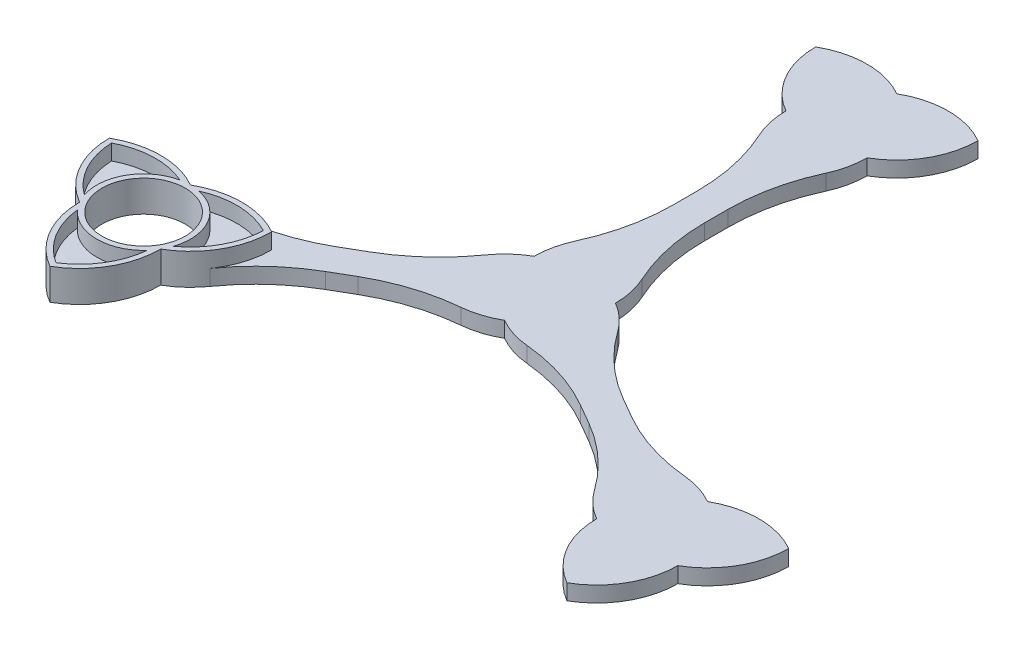
SolidWorks part; units mm, degrees
ref_plane "Front Plane" through (0, 0, 0) normal (0, 0, 1) x (1, 0, 0)
ref_plane "Top Plane" through (0, 0, 0) normal (0, 1, 0) x (1, 0, 0)
ref_plane "Right Plane" through (0, 0, 0) normal (1, 0, 0) x (0, 0, -1)
sketch "Sketch3" plane through (0, 0, 0) normal (0, 1, 0) x (1, 0, 0)
  line L0 (24.8205, 42.9904) -> (17.3205, 30) construction
  line L4 (0, 75.3205) -> (-15.5885, 48.3205) construction
  line L5 (-15.5885, 48.3205) -> (15.5885, 48.3205) construction
  line L6 (15.5885, 48.3205) -> (0, 75.3205) construction
  line L7 (-3, 83.7206) -> (-3, 85.9808)
  line L8 (3, 83.7206) -> (3, 85.9808)
  line L9 (24.8205, 42.9904) -> (26.3205, 45.5885) construction
  line L10 (15.5885, 48.3205) -> (24.8205, 42.9904) construction
  line L11 (24.3632, 46.7185) -> (26.3205, 45.5885)
  line L12 (21.3632, 41.5224) -> (23.3205, 40.3923)
  line L13 (0, 57.3205) -> (0, 40) construction
  line L14 (-21.3632, 41.5224) -> (-23.3205, 40.3923)
  line L15 (-24.3632, 46.7185) -> (-26.3205, 45.5885)
  line L17 (28.2778, 44.4584) -> (26.3205, 45.5885)
  line L18 (65.2295, 37.6603) -> (34.0526, 37.6603) construction
  line L19 (34.0526, 37.6603) -> (49.641, 10.6603) construction
  line L20 (49.641, 10.6603) -> (65.2295, 37.6603) construction
  line L21 (25.2778, 39.2622) -> (23.3205, 40.3923)
  line L25 (-3, 88.2409) -> (-3, 85.9808)
  line L26 (3, 88.2409) -> (3, 85.9808)
  line L27 (0, 85.9808) -> (15, 85.9808) construction
  line L32 (0, 85.9808) -> (-3, 85.9808) construction
  line L33 (-15.5885, 123.641) -> (0, 96.641) construction
  line L34 (0, 96.641) -> (15.5885, 123.641) construction
  line L39 (15.5885, 123.641) -> (-15.5885, 123.641) construction
  line L40 (0, 75.3205) -> (0, 85.9808) construction
  line L41 (0, 57.3205) -> (6.3532, 46.2988) construction
  line L44 (-28.2778, 44.4584) -> (-26.3205, 45.5885)
  line L46 (-65.2295, 37.6603) -> (-49.641, 10.6603) construction
  line L47 (-49.641, 10.6603) -> (-34.0526, 37.6603) construction
  line L48 (-34.0526, 37.6603) -> (-65.2295, 37.6603) construction
  line L50 (-25.2778, 39.2622) -> (-23.3205, 40.3923)
  line L51 (52.641, 2.2601) -> (52.641, 0) [skipped]
  line L52 (46.641, 2.2601) -> (46.641, 0) [skipped]
  line L53 (28.2778, -44.4584) -> (26.3205, -45.5885) [skipped]
  line L54 (52.641, -2.2601) -> (52.641, 0) [skipped]
  line L55 (46.641, -2.2601) -> (46.641, 0) [skipped]
  line L56 (25.2778, -39.2622) -> (23.3205, -40.3923) [skipped]
  line L57 (-24.3632, -46.7185) -> (-26.3205, -45.5885) [skipped]
  line L58 (24.3632, -46.7185) -> (26.3205, -45.5885) [skipped]
  line L59 (21.3632, -41.5224) -> (23.3205, -40.3923) [skipped]
  line L60 (-21.3632, -41.5224) -> (-23.3205, -40.3923) [skipped]
  line L61 (-52.641, -2.2601) -> (-52.641, 0) [skipped]
  line L62 (-28.2778, -44.4584) -> (-26.3205, -45.5885) [skipped]
  line L63 (-25.2778, -39.2622) -> (-23.3205, -40.3923) [skipped]
  line L64 (-46.641, -2.2601) -> (-46.641, 0) [skipped]
  line L65 (-52.641, 2.2601) -> (-52.641, 0) [skipped]
  line L66 (-46.641, 2.2601) -> (-46.641, 0) [skipped]
  line L67 (65.2295, -37.6603) -> (49.641, -10.6603) construction
  line L68 (49.641, -10.6603) -> (34.0526, -37.6603) construction
  line L69 (34.0526, -37.6603) -> (65.2295, -37.6603) construction
  line L70 (0, -75.3205) -> (15.5885, -48.3205) construction
  line L71 (15.5885, -48.3205) -> (-15.5885, -48.3205) construction
  line L72 (-15.5885, -48.3205) -> (0, -75.3205) construction
  line L73 (-34.0526, -37.6603) -> (-49.641, -10.6603) construction
  line L74 (-65.2295, -37.6603) -> (-34.0526, -37.6603) construction
  line L75 (-49.641, -10.6603) -> (-65.2295, -37.6603) construction
  line L76 (0, 57.3205) -> (6.3685, 68.3334) construction
  circle A1 centre (0, 57.3205) radius 9 construction
  arc A2 (0, 75.3205) -> (-7.7942, 61.8205) centre (7.7942, 61.8205) ccw
  arc A3 (0, 75.3205) -> (7.7942, 61.8205) centre (-7.7942, 61.8205) cw
  arc A4 (-12.7217, 57.3293) -> (-7.7942, 61.8205) centre (0, 48.3205) cw
  arc A5 (7.7942, 61.8205) -> (12.7217, 57.3293) centre (0, 48.3205) cw
  arc A6 (-7.7942, 61.8205) -> (7.7942, 61.8205) centre (0, 48.3205) cw construction
  arc A7 (0, 48.3205) -> (6.3532, 46.2988) centre (7.7942, 61.8205) ccw
  arc A8 (-7.7942, 61.8205) -> (0, 48.3205) centre (7.7942, 61.8205) ccw construction
  arc A9 (0, 48.3205) -> (-6.3532, 46.2988) centre (-7.7942, 61.8205) cw
  arc A10 (7.7942, 61.8205) -> (0, 48.3205) centre (-7.7942, 61.8205) cw construction
  arc A11 (12.7217, 57.3293) -> (24.3632, 46.7185) centre (42.7775, 78.6131) ccw
  arc A12 (6.3532, 46.2988) -> (21.3632, 41.5224) centre (2.9488, 9.6278) cw
  arc A13 (-6.3532, 46.2988) -> (-21.3632, 41.5224) centre (-2.9488, 9.6278) ccw
  arc A14 (-12.7217, 57.3293) -> (-24.3632, 46.7185) centre (-42.7775, 78.6131) cw
  arc A15 (12.7217, 57.3293) -> (15.5885, 48.3205) centre (0, 48.3205) cw construction
  arc A16 (6.3532, 46.2988) -> (15.5885, 48.3205) centre (7.7942, 61.8205) ccw construction
  arc A17 (-6.3532, 46.2988) -> (-15.5885, 48.3205) centre (-7.7942, 61.8205) cw construction
  arc A18 (-15.5885, 48.3205) -> (-12.7217, 57.3293) centre (0, 48.3205) cw construction
  arc A19 (65.2295, 37.6603) -> (49.641, 37.6603) centre (57.4352, 24.1603) ccw
  arc A20 (65.2295, 37.6603) -> (57.4352, 24.1603) centre (49.641, 37.6603) cw
  arc A21 (43.2878, 39.682) -> (49.641, 37.6603) centre (41.8468, 24.1603) cw
  arc A22 (57.4352, 24.1603) -> (56.0095, 17.6473) centre (41.8468, 24.1603) cw
  arc A23 (41.8468, 24.1603) -> (43.2726, 17.6473) centre (57.4352, 24.1603) ccw
  arc A24 (41.8468, 24.1603) -> (36.9193, 28.6515) centre (49.641, 37.6603) cw
  arc A27 (36.9193, 28.6515) -> (25.2778, 39.2622) centre (6.8635, 7.3677) ccw
  arc A28 (43.2878, 39.682) -> (28.2778, 44.4584) centre (46.6922, 76.353) cw
  circle A29 centre (49.641, 28.6603) radius 9 construction
  arc A30 (49.641, 37.6603) -> (57.4352, 24.1603) centre (41.8468, 24.1603) cw construction
  arc A31 (49.641, 37.6603) -> (41.8468, 24.1603) centre (57.4352, 24.1603) ccw construction
  arc A32 (57.4352, 24.1603) -> (41.8468, 24.1603) centre (49.641, 37.6603) cw construction
  arc A33 (56.0095, 17.6473) -> (49.641, 10.6603) centre (41.8468, 24.1603) cw
  arc A34 (43.2726, 17.6473) -> (49.641, 10.6603) centre (57.4352, 24.1603) ccw
  arc A35 (36.9193, 28.6515) -> (34.0526, 37.6603) centre (49.641, 37.6603) cw construction
  arc A36 (34.0526, 37.6603) -> (43.2878, 39.682) centre (41.8468, 24.1603) cw construction
  arc A47 (-6.3685, 68.3334) -> (-3, 83.7206) centre (-39.8287, 83.7206) ccw
  arc A51 (6.3685, 68.3334) -> (3, 83.7206) centre (39.8287, 83.7206) cw
  arc A52 (-15.5885, 123.641) -> (-7.7942, 110.141) centre (0, 123.641) ccw
  arc A53 (-15.5885, 123.641) -> (0, 123.641) centre (-7.7942, 110.141) cw
  arc A54 (-6.3685, 103.6281) -> (-7.7942, 110.141) centre (7.7942, 110.141) cw
  arc A65 (0, 123.641) -> (6.3532, 125.6627) centre (7.7942, 110.141) cw
  arc A69 (7.7942, 110.141) -> (12.7217, 114.6322) centre (0, 123.641) ccw
  arc A70 (7.7942, 110.141) -> (6.3685, 103.6281) centre (-7.7942, 110.141) cw
  arc A71 (6.3685, 103.6281) -> (3, 88.2409) centre (39.8287, 88.2409) ccw
  arc A72 (-6.3685, 103.6281) -> (-3, 88.2409) centre (-39.8287, 88.2409) cw
  circle A83 centre (0, 114.641) radius 9 construction
  arc A87 (-7.7942, 110.141) -> (0, 123.641) centre (7.7942, 110.141) cw construction
  arc A88 (-7.7942, 110.141) -> (7.7942, 110.141) centre (0, 123.641) ccw construction
  arc A89 (0, 123.641) -> (7.7942, 110.141) centre (-7.7942, 110.141) cw construction
  arc A90 (6.3532, 125.6627) -> (15.5885, 123.641) centre (7.7942, 110.141) cw
  arc A91 (-65.2295, 37.6603) -> (-57.4352, 24.1603) centre (-49.641, 37.6603) ccw
  arc A92 (-65.2295, 37.6603) -> (-49.641, 37.6603) centre (-57.4352, 24.1603) cw
  arc A93 (-56.0095, 17.6473) -> (-57.4352, 24.1603) centre (-41.8468, 24.1603) cw
  arc A94 (-49.641, 37.6603) -> (-43.2878, 39.682) centre (-41.8468, 24.1603) cw
  arc A95 (-41.8468, 24.1603) -> (-36.9193, 28.6515) centre (-49.641, 37.6603) ccw
  arc A96 (-41.8468, 24.1603) -> (-43.2726, 17.6473) centre (-57.4352, 24.1603) cw
  arc A97 (-43.2878, 39.682) -> (-28.2778, 44.4584) centre (-46.6922, 76.353) ccw
  arc A98 (-36.9193, 28.6515) -> (-25.2778, 39.2622) centre (-6.8635, 7.3677) cw
  circle A101 centre (-49.641, 28.6603) radius 9 construction
  arc A102 (-57.4352, 24.1603) -> (-49.641, 37.6603) centre (-41.8468, 24.1603) cw construction
  arc A103 (-57.4352, 24.1603) -> (-41.8468, 24.1603) centre (-49.641, 37.6603) ccw construction
  arc A104 (-49.641, 37.6603) -> (-41.8468, 24.1603) centre (-57.4352, 24.1603) cw construction
  arc A105 (-43.2878, 39.682) -> (-34.0526, 37.6603) centre (-41.8468, 24.1603) cw construction
  arc A106 (-36.9193, 28.6515) -> (-34.0526, 37.6603) centre (-49.641, 37.6603) ccw construction
  arc A107 (-43.2726, 17.6473) -> (-49.641, 10.6603) centre (-57.4352, 24.1603) cw
  arc A108 (-49.641, 10.6603) -> (-56.0095, 17.6473) centre (-41.8468, 24.1603) cw
  arc A109 (65.2295, -37.6603) -> (57.4352, -24.1603) centre (49.641, -37.6603) ccw [skipped]
  arc A110 (65.2295, -37.6603) -> (49.641, -37.6603) centre (57.4352, -24.1603) cw [skipped]
  arc A111 (56.0095, -17.6473) -> (57.4352, -24.1603) centre (41.8468, -24.1603) cw [skipped]
  arc A112 (49.641, -37.6603) -> (43.2878, -39.682) centre (41.8468, -24.1603) cw [skipped]
  arc A113 (41.8468, -24.1603) -> (36.9193, -28.6515) centre (49.641, -37.6603) ccw [skipped]
  arc A114 (41.8468, -24.1603) -> (43.2726, -17.6473) centre (57.4352, -24.1603) cw [skipped]
  arc A115 (43.2878, -39.682) -> (28.2778, -44.4584) centre (46.6922, -76.353) ccw [skipped]
  arc A116 (36.9193, -28.6515) -> (25.2778, -39.2622) centre (6.8635, -7.3677) cw [skipped]
  arc A117 (43.2726, -17.6473) -> (46.641, -2.2601) centre (9.8123, -2.2601) ccw [skipped]
  arc A118 (56.0095, -17.6473) -> (52.641, -2.2601) centre (89.4697, -2.2601) cw [skipped]
  arc A119 (0, -75.3205) -> (7.7942, -61.8205) centre (-7.7942, -61.8205) ccw [skipped]
  arc A120 (0, -75.3205) -> (-7.7942, -61.8205) centre (7.7942, -61.8205) cw [skipped]
  arc A121 (12.7217, -57.3293) -> (7.7942, -61.8205) centre (0, -48.3205) cw [skipped]
  arc A122 (-7.7942, -61.8205) -> (-12.7217, -57.3293) centre (0, -48.3205) cw [skipped]
  arc A123 (0, -48.3205) -> (-6.3532, -46.2988) centre (-7.7942, -61.8205) ccw [skipped]
  arc A124 (0, -48.3205) -> (6.3532, -46.2988) centre (7.7942, -61.8205) cw [skipped]
  arc A125 (-12.7217, -57.3293) -> (-24.3632, -46.7185) centre (-42.7775, -78.6131) ccw [skipped]
  arc A126 (-6.3532, -46.2988) -> (-21.3632, -41.5224) centre (-2.9488, -9.6278) cw [skipped]
  arc A127 (6.3532, -46.2988) -> (21.3632, -41.5224) centre (2.9488, -9.6278) ccw [skipped]
  arc A128 (12.7217, -57.3293) -> (24.3632, -46.7185) centre (42.7775, -78.6131) cw [skipped]
  arc A129 (-43.2878, -39.682) -> (-49.641, -37.6603) centre (-41.8468, -24.1603) cw [skipped]
  arc A130 (-57.4352, -24.1603) -> (-56.0095, -17.6473) centre (-41.8468, -24.1603) cw [skipped]
  arc A131 (-41.8468, -24.1603) -> (-43.2726, -17.6473) centre (-57.4352, -24.1603) ccw [skipped]
  arc A132 (-41.8468, -24.1603) -> (-36.9193, -28.6515) centre (-49.641, -37.6603) cw [skipped]
  arc A133 (-56.0095, -17.6473) -> (-52.641, -2.2601) centre (-89.4697, -2.2601) ccw [skipped]
  arc A134 (-43.2726, -17.6473) -> (-46.641, -2.2601) centre (-9.8123, -2.2601) cw [skipped]
  arc A135 (-36.9193, -28.6515) -> (-25.2778, -39.2622) centre (-6.8635, -7.3677) ccw [skipped]
  arc A136 (-43.2878, -39.682) -> (-28.2778, -44.4584) centre (-46.6922, -76.353) cw [skipped]
  circle A137 centre (49.641, -28.6603) radius 9 construction
  arc A138 (57.4352, -24.1603) -> (49.641, -37.6603) centre (41.8468, -24.1603) cw construction
  arc A139 (57.4352, -24.1603) -> (41.8468, -24.1603) centre (49.641, -37.6603) ccw construction
  arc A140 (49.641, -37.6603) -> (41.8468, -24.1603) centre (57.4352, -24.1603) cw construction
  arc A141 (43.2878, -39.682) -> (34.0526, -37.6603) centre (41.8468, -24.1603) cw construction
  arc A142 (36.9193, -28.6515) -> (34.0526, -37.6603) centre (49.641, -37.6603) ccw construction
  arc A143 (43.2726, -17.6473) -> (49.641, -10.6603) centre (57.4352, -24.1603) cw construction
  arc A144 (49.641, -10.6603) -> (56.0095, -17.6473) centre (41.8468, -24.1603) cw construction
  circle A145 centre (0, -57.3205) radius 9 construction
  arc A146 (7.7942, -61.8205) -> (-7.7942, -61.8205) centre (0, -48.3205) cw construction
  arc A147 (7.7942, -61.8205) -> (0, -48.3205) centre (-7.7942, -61.8205) ccw construction
  arc A148 (-7.7942, -61.8205) -> (0, -48.3205) centre (7.7942, -61.8205) cw construction
  arc A149 (-12.7217, -57.3293) -> (-15.5885, -48.3205) centre (0, -48.3205) cw construction
  arc A150 (-6.3532, -46.2988) -> (-15.5885, -48.3205) centre (-7.7942, -61.8205) ccw construction
  arc A151 (6.3532, -46.2988) -> (15.5885, -48.3205) centre (7.7942, -61.8205) cw construction
  arc A152 (15.5885, -48.3205) -> (12.7217, -57.3293) centre (0, -48.3205) cw construction
  circle A153 centre (-49.641, -28.6603) radius 9 construction
  arc A154 (-49.641, -37.6603) -> (-57.4352, -24.1603) centre (-41.8468, -24.1603) cw construction
  arc A155 (-49.641, -37.6603) -> (-41.8468, -24.1603) centre (-57.4352, -24.1603) ccw construction
  arc A156 (-57.4352, -24.1603) -> (-41.8468, -24.1603) centre (-49.641, -37.6603) cw construction
  arc A157 (-56.0095, -17.6473) -> (-49.641, -10.6603) centre (-41.8468, -24.1603) cw construction
  arc A158 (-43.2726, -17.6473) -> (-49.641, -10.6603) centre (-57.4352, -24.1603) ccw construction
  arc A159 (-36.9193, -28.6515) -> (-34.0526, -37.6603) centre (-49.641, -37.6603) cw construction
  arc A160 (-34.0526, -37.6603) -> (-43.2878, -39.682) centre (-41.8468, -24.1603) cw construction
  arc A161 (-65.2295, -37.6603) -> (-49.641, -37.6603) centre (-57.4352, -24.1603) ccw [skipped]
  arc A162 (-65.2295, -37.6603) -> (-57.4352, -24.1603) centre (-49.641, -37.6603) cw [skipped]
  arc A163 (-56.0095, 17.6473) -> (-52.641, 2.2601) centre (-89.4697, 2.2601) cw [skipped]
  arc A164 (-43.2726, 17.6473) -> (-46.641, 2.2601) centre (-9.8123, 2.2601) ccw [skipped]
  arc A165 (43.2726, 17.6473) -> (46.641, 2.2601) centre (9.8123, 2.2601) cw [skipped]
  arc A166 (56.0095, 17.6473) -> (52.641, 2.2601) centre (89.4697, 2.2601) ccw [skipped]
  arc A167 (12.7217, 114.6322) -> (15.5885, 123.641) centre (0, 123.641) ccw
  arc A168 (6.3685, 103.6281) -> (0, 96.641) centre (-7.7942, 110.141) cw construction
  arc A169 (0, 96.641) -> (-6.3685, 103.6281) centre (7.7942, 110.141) cw construction
  dimension "D1" = 18
  dimension "D2" = 6
  dimension "D3" = 3
  dimension "D4" = 2
  dimension "D5" = 120
extrude "Boss-Extrude2" add sketch "Sketch3" along normal blind 3 contours A108 A107 A96 A95 A98 L50 L14 A13 A9 A7 A12 L12 L21 A27 A24 A23 A34 A33 A22 A20 A19 A21 A28 L17 L11 A11 A5 A3 A2 A4 A14 L15 L44 A97 A94 A92 A91 A93 | A69 A167 A90 A65 A53 A52 A54 A72 L25 L7 A47 A2 A3 A51 L8 L26 A71 A70
ref_plane "Plane1" through (0, 3, 0) normal (0, 1, 0) x (1, 0, 0)
sketch "Sketch10" plane through (0, 3, 0) normal (0, 1, 0) x (1, 0, 0)
  line L0 (24.8205, 42.9904) -> (17.3205, 30) construction
  line L4 (0, 75.3205) -> (-15.5885, 48.3205) construction
  line L5 (-15.5885, 48.3205) -> (15.5885, 48.3205) construction
  line L6 (15.5885, 48.3205) -> (0, 75.3205) construction
  line L7 (-3, 83.7206) -> (-3, 85.9808)
  line L8 (3, 83.7206) -> (3, 85.9808)
  line L9 (24.8205, 42.9904) -> (26.3205, 45.5885) construction
  line L10 (15.5885, 48.3205) -> (24.8205, 42.9904) construction
  line L11 (24.3632, 46.7185) -> (26.3205, 45.5885)
  line L12 (21.3632, 41.5224) -> (23.3205, 40.3923)
  line L13 (0, 57.3205) -> (0, 40) construction
  line L14 (-21.3632, 41.5224) -> (-23.3205, 40.3923)
  line L15 (-24.3632, 46.7185) -> (-26.3205, 45.5885)
  line L17 (28.2778, 44.4584) -> (26.3205, 45.5885)
  line L18 (65.2295, 37.6603) -> (34.0526, 37.6603) construction
  line L19 (34.0526, 37.6603) -> (49.641, 10.6603) construction
  line L20 (49.641, 10.6603) -> (65.2295, 37.6603) construction
  line L21 (25.2778, 39.2622) -> (23.3205, 40.3923)
  line L25 (-3, 88.2409) -> (-3, 85.9808)
  line L26 (3, 88.2409) -> (3, 85.9808)
  line L27 (0, 85.9808) -> (15, 85.9808) construction
  line L32 (0, 85.9808) -> (-3, 85.9808) construction
  line L33 (-15.5885, 123.641) -> (0, 96.641) construction
  line L34 (0, 96.641) -> (15.5885, 123.641) construction
  line L39 (15.5885, 123.641) -> (-15.5885, 123.641) construction
  line L40 (0, 75.3205) -> (0, 85.9808) construction
  line L41 (0, 57.3205) -> (6.3532, 46.2988) construction
  line L44 (-28.2778, 44.4584) -> (-26.3205, 45.5885)
  line L46 (-65.2295, 37.6603) -> (-49.641, 10.6603) construction
  line L47 (-49.641, 10.6603) -> (-34.0526, 37.6603) construction
  line L48 (-34.0526, 37.6603) -> (-65.2295, 37.6603) construction
  line L50 (-25.2778, 39.2622) -> (-23.3205, 40.3923)
  line L51 (52.641, 2.2601) -> (52.641, 0)
  line L52 (46.641, 2.2601) -> (46.641, 0)
  line L53 (28.2778, -44.4584) -> (26.3205, -45.5885)
  line L54 (52.641, -2.2601) -> (52.641, 0)
  line L55 (46.641, -2.2601) -> (46.641, 0)
  line L56 (25.2778, -39.2622) -> (23.3205, -40.3923)
  line L57 (-24.3632, -46.7185) -> (-26.3205, -45.5885)
  line L58 (24.3632, -46.7185) -> (26.3205, -45.5885)
  line L59 (21.3632, -41.5224) -> (23.3205, -40.3923)
  line L60 (-21.3632, -41.5224) -> (-23.3205, -40.3923)
  line L61 (-52.641, -2.2601) -> (-52.641, 0)
  line L62 (-28.2778, -44.4584) -> (-26.3205, -45.5885)
  line L63 (-25.2778, -39.2622) -> (-23.3205, -40.3923)
  line L64 (-46.641, -2.2601) -> (-46.641, 0)
  line L65 (-52.641, 2.2601) -> (-52.641, 0)
  line L66 (-46.641, 2.2601) -> (-46.641, 0)
  line L67 (65.2295, -37.6603) -> (49.641, -10.6603) construction
  line L68 (49.641, -10.6603) -> (34.0526, -37.6603) construction
  line L69 (34.0526, -37.6603) -> (65.2295, -37.6603) construction
  line L70 (0, -75.3205) -> (15.5885, -48.3205) construction
  line L71 (15.5885, -48.3205) -> (-15.5885, -48.3205) construction
  line L72 (-15.5885, -48.3205) -> (0, -75.3205) construction
  line L73 (-34.0526, -37.6603) -> (-49.641, -10.6603) construction
  line L74 (-65.2295, -37.6603) -> (-34.0526, -37.6603) construction
  line L75 (-49.641, -10.6603) -> (-65.2295, -37.6603) construction
  line L76 (0, 57.3205) -> (6.3685, 68.3334) construction
  circle A1 centre (0, 57.3205) radius 9 construction
  arc A2 (0, 75.3205) -> (-7.7942, 61.8205) centre (7.7942, 61.8205) ccw
  arc A3 (0, 75.3205) -> (7.7942, 61.8205) centre (-7.7942, 61.8205) cw
  arc A4 (-12.7217, 57.3293) -> (-7.7942, 61.8205) centre (0, 48.3205) cw
  arc A5 (7.7942, 61.8205) -> (12.7217, 57.3293) centre (0, 48.3205) cw
  arc A6 (-7.7942, 61.8205) -> (7.7942, 61.8205) centre (0, 48.3205) cw construction
  arc A7 (0, 48.3205) -> (6.3532, 46.2988) centre (7.7942, 61.8205) ccw
  arc A8 (-7.7942, 61.8205) -> (0, 48.3205) centre (7.7942, 61.8205) ccw construction
  arc A9 (0, 48.3205) -> (-6.3532, 46.2988) centre (-7.7942, 61.8205) cw
  arc A10 (7.7942, 61.8205) -> (0, 48.3205) centre (-7.7942, 61.8205) cw construction
  arc A11 (12.7217, 57.3293) -> (24.3632, 46.7185) centre (42.7775, 78.6131) ccw
  arc A12 (6.3532, 46.2988) -> (21.3632, 41.5224) centre (2.9488, 9.6278) cw
  arc A13 (-6.3532, 46.2988) -> (-21.3632, 41.5224) centre (-2.9488, 9.6278) ccw
  arc A14 (-12.7217, 57.3293) -> (-24.3632, 46.7185) centre (-42.7775, 78.6131) cw
  arc A15 (12.7217, 57.3293) -> (15.5885, 48.3205) centre (0, 48.3205) cw construction
  arc A16 (6.3532, 46.2988) -> (15.5885, 48.3205) centre (7.7942, 61.8205) ccw construction
  arc A17 (-6.3532, 46.2988) -> (-15.5885, 48.3205) centre (-7.7942, 61.8205) cw construction
  arc A18 (-15.5885, 48.3205) -> (-12.7217, 57.3293) centre (0, 48.3205) cw construction
  arc A19 (65.2295, 37.6603) -> (49.641, 37.6603) centre (57.4352, 24.1603) ccw
  arc A20 (65.2295, 37.6603) -> (57.4352, 24.1603) centre (49.641, 37.6603) cw
  arc A21 (43.2878, 39.682) -> (49.641, 37.6603) centre (41.8468, 24.1603) cw
  arc A22 (57.4352, 24.1603) -> (56.0095, 17.6473) centre (41.8468, 24.1603) cw
  arc A23 (41.8468, 24.1603) -> (43.2726, 17.6473) centre (57.4352, 24.1603) ccw
  arc A24 (41.8468, 24.1603) -> (36.9193, 28.6515) centre (49.641, 37.6603) cw
  arc A27 (36.9193, 28.6515) -> (25.2778, 39.2622) centre (6.8635, 7.3677) ccw
  arc A28 (43.2878, 39.682) -> (28.2778, 44.4584) centre (46.6922, 76.353) cw
  circle A29 centre (49.641, 28.6603) radius 9 construction
  arc A30 (49.641, 37.6603) -> (57.4352, 24.1603) centre (41.8468, 24.1603) cw construction
  arc A31 (49.641, 37.6603) -> (41.8468, 24.1603) centre (57.4352, 24.1603) ccw construction
  arc A32 (57.4352, 24.1603) -> (41.8468, 24.1603) centre (49.641, 37.6603) cw construction
  arc A33 (56.0095, 17.6473) -> (49.641, 10.6603) centre (41.8468, 24.1603) cw
  arc A34 (43.2726, 17.6473) -> (49.641, 10.6603) centre (57.4352, 24.1603) ccw
  arc A35 (36.9193, 28.6515) -> (34.0526, 37.6603) centre (49.641, 37.6603) cw construction
  arc A36 (34.0526, 37.6603) -> (43.2878, 39.682) centre (41.8468, 24.1603) cw construction
  arc A47 (-6.3685, 68.3334) -> (-3, 83.7206) centre (-39.8287, 83.7206) ccw
  arc A51 (6.3685, 68.3334) -> (3, 83.7206) centre (39.8287, 83.7206) cw
  arc A52 (-15.5885, 123.641) -> (-7.7942, 110.141) centre (0, 123.641) ccw
  arc A53 (-15.5885, 123.641) -> (0, 123.641) centre (-7.7942, 110.141) cw
  arc A54 (-6.3685, 103.6281) -> (-7.7942, 110.141) centre (7.7942, 110.141) cw
  arc A65 (0, 123.641) -> (6.3532, 125.6627) centre (7.7942, 110.141) cw
  arc A69 (7.7942, 110.141) -> (12.7217, 114.6322) centre (0, 123.641) ccw
  arc A70 (7.7942, 110.141) -> (6.3685, 103.6281) centre (-7.7942, 110.141) cw
  arc A71 (6.3685, 103.6281) -> (3, 88.2409) centre (39.8287, 88.2409) ccw
  arc A72 (-6.3685, 103.6281) -> (-3, 88.2409) centre (-39.8287, 88.2409) cw
  circle A83 centre (0, 114.641) radius 9 construction
  arc A87 (-7.7942, 110.141) -> (0, 123.641) centre (7.7942, 110.141) cw construction
  arc A88 (-7.7942, 110.141) -> (7.7942, 110.141) centre (0, 123.641) ccw construction
  arc A89 (0, 123.641) -> (7.7942, 110.141) centre (-7.7942, 110.141) cw construction
  arc A90 (6.3532, 125.6627) -> (15.5885, 123.641) centre (7.7942, 110.141) cw
  arc A91 (-65.2295, 37.6603) -> (-57.4352, 24.1603) centre (-49.641, 37.6603) ccw
  arc A92 (-65.2295, 37.6603) -> (-49.641, 37.6603) centre (-57.4352, 24.1603) cw
  arc A93 (-56.0095, 17.6473) -> (-57.4352, 24.1603) centre (-41.8468, 24.1603) cw
  arc A94 (-49.641, 37.6603) -> (-43.2878, 39.682) centre (-41.8468, 24.1603) cw
  arc A95 (-41.8468, 24.1603) -> (-36.9193, 28.6515) centre (-49.641, 37.6603) ccw
  arc A96 (-41.8468, 24.1603) -> (-43.2726, 17.6473) centre (-57.4352, 24.1603) cw
  arc A97 (-43.2878, 39.682) -> (-28.2778, 44.4584) centre (-46.6922, 76.353) ccw
  arc A98 (-36.9193, 28.6515) -> (-25.2778, 39.2622) centre (-6.8635, 7.3677) cw
  circle A101 centre (-49.641, 28.6603) radius 9 construction
  arc A102 (-57.4352, 24.1603) -> (-49.641, 37.6603) centre (-41.8468, 24.1603) cw construction
  arc A103 (-57.4352, 24.1603) -> (-41.8468, 24.1603) centre (-49.641, 37.6603) ccw construction
  arc A104 (-49.641, 37.6603) -> (-41.8468, 24.1603) centre (-57.4352, 24.1603) cw construction
  arc A105 (-43.2878, 39.682) -> (-34.0526, 37.6603) centre (-41.8468, 24.1603) cw construction
  arc A106 (-36.9193, 28.6515) -> (-34.0526, 37.6603) centre (-49.641, 37.6603) ccw construction
  arc A107 (-43.2726, 17.6473) -> (-49.641, 10.6603) centre (-57.4352, 24.1603) cw
  arc A108 (-49.641, 10.6603) -> (-56.0095, 17.6473) centre (-41.8468, 24.1603) cw
  arc A109 (65.2295, -37.6603) -> (57.4352, -24.1603) centre (49.641, -37.6603) ccw
  arc A110 (65.2295, -37.6603) -> (49.641, -37.6603) centre (57.4352, -24.1603) cw
  arc A111 (56.0095, -17.6473) -> (57.4352, -24.1603) centre (41.8468, -24.1603) cw
  arc A112 (49.641, -37.6603) -> (43.2878, -39.682) centre (41.8468, -24.1603) cw
  arc A113 (41.8468, -24.1603) -> (36.9193, -28.6515) centre (49.641, -37.6603) ccw
  arc A114 (41.8468, -24.1603) -> (43.2726, -17.6473) centre (57.4352, -24.1603) cw
  arc A115 (43.2878, -39.682) -> (28.2778, -44.4584) centre (46.6922, -76.353) ccw
  arc A116 (36.9193, -28.6515) -> (25.2778, -39.2622) centre (6.8635, -7.3677) cw
  arc A117 (43.2726, -17.6473) -> (46.641, -2.2601) centre (9.8123, -2.2601) ccw
  arc A118 (56.0095, -17.6473) -> (52.641, -2.2601) centre (89.4697, -2.2601) cw
  arc A119 (0, -75.3205) -> (7.7942, -61.8205) centre (-7.7942, -61.8205) ccw
  arc A120 (0, -75.3205) -> (-7.7942, -61.8205) centre (7.7942, -61.8205) cw
  arc A121 (12.7217, -57.3293) -> (7.7942, -61.8205) centre (0, -48.3205) cw
  arc A122 (-7.7942, -61.8205) -> (-12.7217, -57.3293) centre (0, -48.3205) cw
  arc A123 (0, -48.3205) -> (-6.3532, -46.2988) centre (-7.7942, -61.8205) ccw
  arc A124 (0, -48.3205) -> (6.3532, -46.2988) centre (7.7942, -61.8205) cw
  arc A125 (-12.7217, -57.3293) -> (-24.3632, -46.7185) centre (-42.7775, -78.6131) ccw
  arc A126 (-6.3532, -46.2988) -> (-21.3632, -41.5224) centre (-2.9488, -9.6278) cw
  arc A127 (6.3532, -46.2988) -> (21.3632, -41.5224) centre (2.9488, -9.6278) ccw
  arc A128 (12.7217, -57.3293) -> (24.3632, -46.7185) centre (42.7775, -78.6131) cw
  arc A129 (-43.2878, -39.682) -> (-49.641, -37.6603) centre (-41.8468, -24.1603) cw
  arc A130 (-57.4352, -24.1603) -> (-56.0095, -17.6473) centre (-41.8468, -24.1603) cw
  arc A131 (-41.8468, -24.1603) -> (-43.2726, -17.6473) centre (-57.4352, -24.1603) ccw
  arc A132 (-41.8468, -24.1603) -> (-36.9193, -28.6515) centre (-49.641, -37.6603) cw
  arc A133 (-56.0095, -17.6473) -> (-52.641, -2.2601) centre (-89.4697, -2.2601) ccw
  arc A134 (-43.2726, -17.6473) -> (-46.641, -2.2601) centre (-9.8123, -2.2601) cw
  arc A135 (-36.9193, -28.6515) -> (-25.2778, -39.2622) centre (-6.8635, -7.3677) ccw
  arc A136 (-43.2878, -39.682) -> (-28.2778, -44.4584) centre (-46.6922, -76.353) cw
  circle A137 centre (49.641, -28.6603) radius 9 construction
  arc A138 (57.4352, -24.1603) -> (49.641, -37.6603) centre (41.8468, -24.1603) cw construction
  arc A139 (57.4352, -24.1603) -> (41.8468, -24.1603) centre (49.641, -37.6603) ccw construction
  arc A140 (49.641, -37.6603) -> (41.8468, -24.1603) centre (57.4352, -24.1603) cw construction
  arc A141 (43.2878, -39.682) -> (34.0526, -37.6603) centre (41.8468, -24.1603) cw construction
  arc A142 (36.9193, -28.6515) -> (34.0526, -37.6603) centre (49.641, -37.6603) ccw construction
  arc A143 (43.2726, -17.6473) -> (49.641, -10.6603) centre (57.4352, -24.1603) cw construction
  arc A144 (49.641, -10.6603) -> (56.0095, -17.6473) centre (41.8468, -24.1603) cw construction
  circle A145 centre (0, -57.3205) radius 9 construction
  arc A146 (7.7942, -61.8205) -> (-7.7942, -61.8205) centre (0, -48.3205) cw construction
  arc A147 (7.7942, -61.8205) -> (0, -48.3205) centre (-7.7942, -61.8205) ccw construction
  arc A148 (-7.7942, -61.8205) -> (0, -48.3205) centre (7.7942, -61.8205) cw construction
  arc A149 (-12.7217, -57.3293) -> (-15.5885, -48.3205) centre (0, -48.3205) cw construction
  arc A150 (-6.3532, -46.2988) -> (-15.5885, -48.3205) centre (-7.7942, -61.8205) ccw construction
  arc A151 (6.3532, -46.2988) -> (15.5885, -48.3205) centre (7.7942, -61.8205) cw construction
  arc A152 (15.5885, -48.3205) -> (12.7217, -57.3293) centre (0, -48.3205) cw construction
  circle A153 centre (-49.641, -28.6603) radius 9 construction
  arc A154 (-49.641, -37.6603) -> (-57.4352, -24.1603) centre (-41.8468, -24.1603) cw construction
  arc A155 (-49.641, -37.6603) -> (-41.8468, -24.1603) centre (-57.4352, -24.1603) ccw construction
  arc A156 (-57.4352, -24.1603) -> (-41.8468, -24.1603) centre (-49.641, -37.6603) cw construction
  arc A157 (-56.0095, -17.6473) -> (-49.641, -10.6603) centre (-41.8468, -24.1603) cw construction
  arc A158 (-43.2726, -17.6473) -> (-49.641, -10.6603) centre (-57.4352, -24.1603) ccw construction
  arc A159 (-36.9193, -28.6515) -> (-34.0526, -37.6603) centre (-49.641, -37.6603) cw construction
  arc A160 (-34.0526, -37.6603) -> (-43.2878, -39.682) centre (-41.8468, -24.1603) cw construction
  arc A161 (-65.2295, -37.6603) -> (-49.641, -37.6603) centre (-57.4352, -24.1603) ccw
  arc A162 (-65.2295, -37.6603) -> (-57.4352, -24.1603) centre (-49.641, -37.6603) cw
  arc A163 (-56.0095, 17.6473) -> (-52.641, 2.2601) centre (-89.4697, 2.2601) cw
  arc A164 (-43.2726, 17.6473) -> (-46.641, 2.2601) centre (-9.8123, 2.2601) ccw
  arc A165 (43.2726, 17.6473) -> (46.641, 2.2601) centre (9.8123, 2.2601) cw
  arc A166 (56.0095, 17.6473) -> (52.641, 2.2601) centre (89.4697, 2.2601) ccw
  arc A167 (12.7217, 114.6322) -> (15.5885, 123.641) centre (0, 123.641) ccw
  arc A168 (6.3685, 103.6281) -> (0, 96.641) centre (-7.7942, 110.141) cw construction
  arc A169 (0, 96.641) -> (-6.3685, 103.6281) centre (7.7942, 110.141) cw construction
  dimension "D1" = 18
  dimension "D2" = 6
  dimension "D3" = 3
  dimension "D4" = 2
  dimension "D5" = 120
sketch "Sketch12" plane through (0, 3, 0) normal (0, 1, 0) x (1, 0, 0)
  circle A0 centre (-49.641, 28.6603) radius 9 construction
  circle A1 centre (-49.641, 28.6603) radius 9 construction
  arc A2 (-57.4352, 24.1603) -> (-56.0095, 17.6473) centre (-41.8468, 24.1603) ccw construction
  arc A3 (-56.0095, 17.6473) -> (-49.641, 10.6603) centre (-41.8468, 24.1603) ccw construction
  arc A4 (-49.641, 10.6603) -> (-43.2726, 17.6473) centre (-57.4352, 24.1603) ccw construction
  arc A5 (-43.2726, 17.6473) -> (-41.8468, 24.1603) centre (-57.4352, 24.1603) ccw construction
  arc A6 (-41.8468, 24.1603) -> (-36.9193, 28.6515) centre (-49.641, 37.6603) ccw construction
  arc A7 (-36.9193, 28.6515) -> (-34.0526, 37.6603) centre (-49.641, 37.6603) ccw construction
  arc A8 (-34.0526, 37.6603) -> (-43.2878, 39.682) centre (-41.8468, 24.1603) ccw construction
  arc A9 (-43.2878, 39.682) -> (-49.641, 37.6603) centre (-41.8468, 24.1603) ccw construction
  arc A10 (-49.641, 37.6603) -> (-65.2295, 37.6603) centre (-57.4352, 24.1603) ccw construction
  arc A11 (-65.2295, 37.6603) -> (-57.4352, 24.1603) centre (-49.641, 37.6603) ccw construction
  arc A12 (-57.4352, 24.1603) -> (-56.0095, 17.6473) centre (-41.8468, 24.1603) ccw
  arc A13 (-56.0095, 17.6473) -> (-49.641, 10.6603) centre (-41.8468, 24.1603) ccw
  arc A14 (-49.641, 10.6603) -> (-43.2726, 17.6473) centre (-57.4352, 24.1603) ccw
  arc A15 (-43.2726, 17.6473) -> (-41.8468, 24.1603) centre (-57.4352, 24.1603) ccw
  arc A16 (-41.8468, 24.1603) -> (-36.9193, 28.6515) centre (-49.641, 37.6603) ccw
  arc A17 (-36.9193, 28.6515) -> (-34.0526, 37.6603) centre (-49.641, 37.6603) ccw
  arc A18 (-34.0526, 37.6603) -> (-43.2878, 39.682) centre (-41.8468, 24.1603) ccw
  arc A19 (-43.2878, 39.682) -> (-49.641, 37.6603) centre (-41.8468, 24.1603) ccw
  arc A20 (-49.641, 37.6603) -> (-65.2295, 37.6603) centre (-57.4352, 24.1603) ccw
  arc A21 (-65.2295, 37.6603) -> (-57.4352, 24.1603) centre (-49.641, 37.6603) ccw
  circle A22 centre (-49.641, 28.6603) radius 8
  circle A23 centre (-49.641, 28.6603) radius 9
  arc A24 (-64.2178, 37.0761) -> (-58.1866, 25.8367) centre (-49.641, 37.6603) ccw
  arc A25 (-56.4235, 24.7444) -> (-56.4327, 24.4326) centre (-41.8468, 24.1603) ccw construction
  arc A26 (-55.1009, 18.0651) -> (-49.641, 11.8285) centre (-41.8468, 24.1603) ccw
  arc A27 (-49.641, 11.8285) -> (-44.1811, 18.0651) centre (-57.4352, 24.1603) ccw
  arc A28 (-44.1811, 18.0651) -> (-42.923, 22.6713) centre (-57.4352, 24.1603) ccw
  arc A29 (-42.8585, 24.7444) -> (-42.5839, 24.8923) centre (-49.641, 37.6603) ccw construction
  arc A30 (-37.7354, 29.2294) -> (-35.0643, 37.0761) centre (-49.641, 37.6603) ccw
  arc A31 (-35.0643, 37.0761) -> (-43.1953, 38.6862) centre (-41.8468, 24.1603) ccw
  arc A32 (-43.1953, 38.6862) -> (-47.8134, 37.4727) centre (-41.8468, 24.1603) ccw
  arc A33 (-49.641, 36.492) -> (-49.9064, 36.6559) centre (-57.4352, 24.1603) ccw construction
  arc A34 (-56.6981, 24.8923) -> (-56.4235, 24.7444) centre (-49.641, 37.6603) ccw construction
  arc A35 (-56.3591, 22.6713) -> (-55.1009, 18.0651) centre (-41.8468, 24.1603) ccw
  arc A36 (-58.1866, 25.8367) -> (-56.6981, 24.8923) centre (-49.641, 37.6603) ccw construction
  arc A37 (-64.2178, 37.0761) -> (-56.4235, 24.7444) centre (-49.641, 37.6603) ccw construction
  arc A38 (-42.8493, 24.4326) -> (-42.8585, 24.7444) centre (-57.4352, 24.1603) ccw construction
  arc A39 (-56.4327, 24.4326) -> (-56.3591, 22.6713) centre (-41.8468, 24.1603) ccw construction
  arc A40 (-56.4235, 24.7444) -> (-55.1009, 18.0651) centre (-41.8468, 24.1603) ccw construction
  arc A41 (-41.0954, 25.8367) -> (-37.7354, 29.2294) centre (-49.641, 37.6603) ccw
  arc A42 (-42.923, 22.6713) -> (-42.8493, 24.4326) centre (-57.4352, 24.1603) ccw construction
  arc A43 (-44.1811, 18.0651) -> (-42.8585, 24.7444) centre (-57.4352, 24.1603) ccw construction
  arc A44 (-49.3756, 36.6559) -> (-49.641, 36.492) centre (-41.8468, 24.1603) ccw construction
  arc A45 (-42.5839, 24.8923) -> (-41.0954, 25.8367) centre (-49.641, 37.6603) ccw construction
  arc A46 (-42.8585, 24.7444) -> (-37.7354, 29.2294) centre (-49.641, 37.6603) ccw construction
  arc A47 (-51.4686, 37.4727) -> (-64.2178, 37.0761) centre (-57.4352, 24.1603) ccw
  arc A48 (-47.8134, 37.4727) -> (-49.3756, 36.6559) centre (-41.8468, 24.1603) ccw construction
  arc A49 (-43.1953, 38.6862) -> (-49.641, 36.492) centre (-41.8468, 24.1603) ccw construction
  arc A51 (-49.9064, 36.6559) -> (-51.4686, 37.4727) centre (-57.4352, 24.1603) ccw construction
  arc A52 (-49.641, 36.492) -> (-64.2178, 37.0761) centre (-57.4352, 24.1603) ccw construction
  dimension "D1" = 16
  dimension "D2" = 18
  dimension "D3" = 1
extrude "Boss-Extrude3" add sketch "Sketch12" along normal blind 3 contours A20 A21 A12 A13 A14 A15 A16 A17 A18 A19 A33 A32 A31 A30 A29 A28 A27 A26 A25 A24 | A23 A22 | A47 A23 A20 A21 A24 | A41 A23 A16 A17 A18 A19 A32 A31 A30
sketch "Sketch13" plane through (0, 3, 0) normal (0, 1, 0) x (1, 0, 0)
  line L0 (-49.641, 37.6603) -> (-49.641, 35.6603) construction
  line L1 (-35.7846, 36.6603) -> (-34.0526, 37.6603) construction
  line L2 (-49.641, 28.6603) -> (-49.641, 36.6603) construction
  line L3 (-49.641, 28.6603) -> (-44.4987, 34.7886) construction
  circle A0 centre (-49.641, 28.6603) radius 8 construction
  arc A1 (-41.8468, 24.1603) -> (-34.0526, 37.6603) centre (-49.641, 37.6603) ccw
  arc A3 (-35.7846, 36.6603) -> (-44.4987, 34.7886) centre (-40.8696, 39.1136) cw
  arc A4 (-35.7846, 36.6603) -> (-41.7626, 30.0494) centre (-36.2024, 31.0298) ccw
  arc A5 (-49.641, 12.6603) -> (-46.9049, 21.1427) centre (-44.9738, 15.8373) cw
  arc A6 (-49.641, 12.6603) -> (-52.3772, 21.1427) centre (-54.3082, 15.8373) ccw
  arc A7 (-63.4974, 36.6603) -> (-57.5195, 30.0494) centre (-63.0796, 31.0298) cw
  arc A8 (-56.3591, 22.6713) -> (-49.641, 11.8285) centre (-41.8468, 24.1603) ccw
  arc A9 (-56.3591, 22.6713) -> (-49.641, 11.8285) centre (-41.8468, 24.1603) ccw
  arc A10 (-56.3591, 22.6713) -> (-42.923, 22.6713) centre (-49.641, 28.6603) ccw
  arc A11 (-49.641, 11.8285) -> (-42.923, 22.6713) centre (-57.4352, 24.1603) ccw
  arc A12 (-56.3591, 22.6713) -> (-42.923, 22.6713) centre (-49.641, 28.6603) ccw
  arc A17 (-49.641, 11.8285) -> (-42.923, 22.6713) centre (-57.4352, 24.1603) ccw construction
  arc A20 (-63.4974, 36.6603) -> (-54.7833, 34.7886) centre (-58.4124, 39.1136) ccw
  arc A25 (-57.4352, 24.1603) -> (-49.641, 10.6603) centre (-41.8468, 24.1603) ccw
  arc A26 (-57.4352, 24.1603) -> (-49.641, 10.6603) centre (-41.8468, 24.1603) ccw
  arc A27 (-49.641, 10.6603) -> (-41.8468, 24.1603) centre (-57.4352, 24.1603) ccw
  arc A28 (-49.641, 10.6603) -> (-41.8468, 24.1603) centre (-57.4352, 24.1603) ccw
  arc A31 (-41.8468, 24.1603) -> (-34.0526, 37.6603) centre (-49.641, 37.6603) ccw
  arc A32 (-34.0526, 37.6603) -> (-49.641, 37.6603) centre (-41.8468, 24.1603) ccw
  arc A33 (-34.0526, 37.6603) -> (-49.641, 37.6603) centre (-41.8468, 24.1603) ccw
  arc A34 (-49.641, 37.6603) -> (-65.2295, 37.6603) centre (-57.4352, 24.1603) ccw
  arc A35 (-49.641, 37.6603) -> (-65.2295, 37.6603) centre (-57.4352, 24.1603) ccw
  arc A36 (-65.2295, 37.6603) -> (-57.4352, 24.1603) centre (-49.641, 37.6603) ccw
  arc A37 (-65.2295, 37.6603) -> (-57.4352, 24.1603) centre (-49.641, 37.6603) ccw
  point P12 (-49.641, 36.6603)
  dimension "D5" = 40
  dimension "D7" = 16
  dimension "D3" = 2
  dimension "D4" = 1.7321
  dimension "D6" = 3
  dimension "D1" = 0
  dimension "D2" = 0
sketch "Sketch15" plane through (0, 3, 0) normal (0, 1, 0) x (1, 0, 0)
  circle A0 centre (-49.641, 28.6603) radius 8
  dimension "D1" = 16
extrude "Cut-Extrude1" cut sketch "Sketch15" against normal blind 3
sketch "Sketch16" plane through (0, 3, 0) normal (0, 1, 0) x (1, 0, 0)
  arc A0 (-34.0526, 37.6603) -> (-43.2878, 39.682) centre (-41.8468, 24.1603) ccw construction
  arc A1 (-36.9193, 28.6515) -> (-34.0526, 37.6603) centre (-49.641, 37.6603) ccw construction
  arc A2 (-34.0526, 37.6603) -> (-43.2878, 39.682) centre (-41.8468, 24.1603) ccw
  arc A3 (-36.9193, 28.6515) -> (-34.0526, 37.6603) centre (-49.641, 37.6603) ccw
split "Split1" trim tools "Sketch16" bodies to split 105 resulting bodies 107 108
